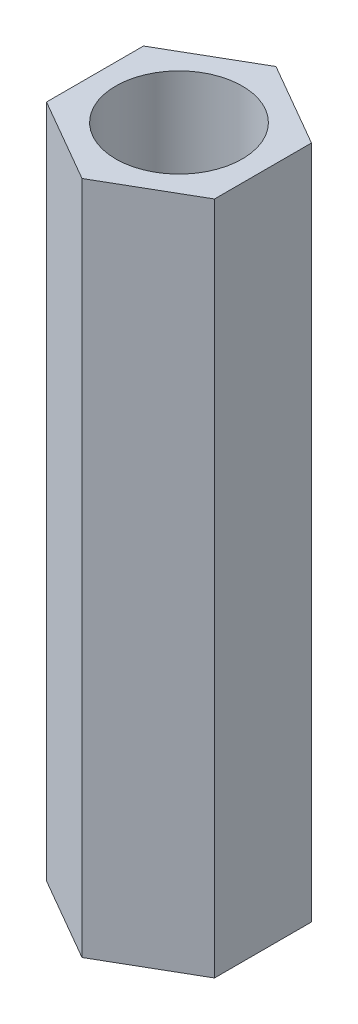
SolidWorks part; units mm, degrees
material "黄铜"
ref_plane "前视基准面" through (0, 0, 0) normal (0, 0, 1) x (1, 0, 0)
ref_plane "上视基准面" through (0, 0, 0) normal (0, 1, 0) x (1, 0, 0)
ref_plane "右视基准面" through (0, 0, 0) normal (1, 0, 0) x (0, 0, -1)
other "Configuration Table"
sketch "草图1" plane through (0, 0, 0) normal (0, 1, 0) x (1, 0, 0)
  line L0 (0, 0) -> (0, 3.1896) construction
  line L1 (1.9919, 1.15) -> (0, 2.3)
  line L2 (0, 2.3) -> (-1.9919, 1.15)
  line L3 (-1.9919, 1.15) -> (-1.9919, -1.15)
  line L4 (-1.9919, -1.15) -> (0, -2.3)
  line L5 (0, -2.3) -> (1.9919, -1.15)
  line L6 (1.9919, -1.15) -> (1.9919, 1.15)
  circle A0 centre (0, 0) radius 1.5
  circle A1 centre (0, 0) radius 1.9919 construction
  dimension "D1" = 3
  dimension "D2" = 4.6
extrude "凸台-拉伸1" add sketch "草图1" along normal blind 16
